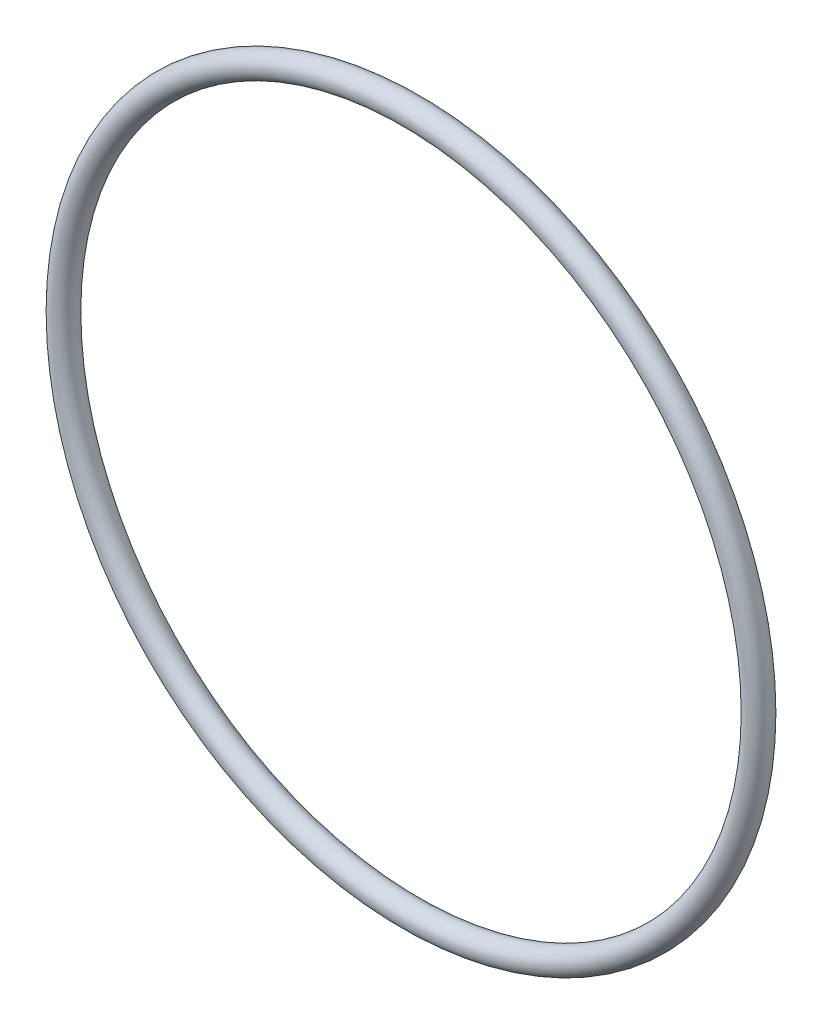
SolidWorks part; units mm, degrees
material "Copper"
ref_plane "Front Plane" through (0, 0, 0) normal (0, 0, 1) x (1, 0, 0)
ref_plane "Top Plane" through (0, 0, 0) normal (0, 1, 0) x (1, 0, 0)
ref_plane "Right Plane" through (0, 0, 0) normal (1, 0, 0) x (0, 0, -1)
sketch "Sketch1" plane through (0, 0, 0) normal (0, 0, 1) x (1, 0, 0)
  circle A0 centre (0, 0) radius 23
  dimension "D1" = 46
sweep "Sweep1" add path "Sketch1" circular profile diameter 1.6256 parameters "D3"=1.6256
